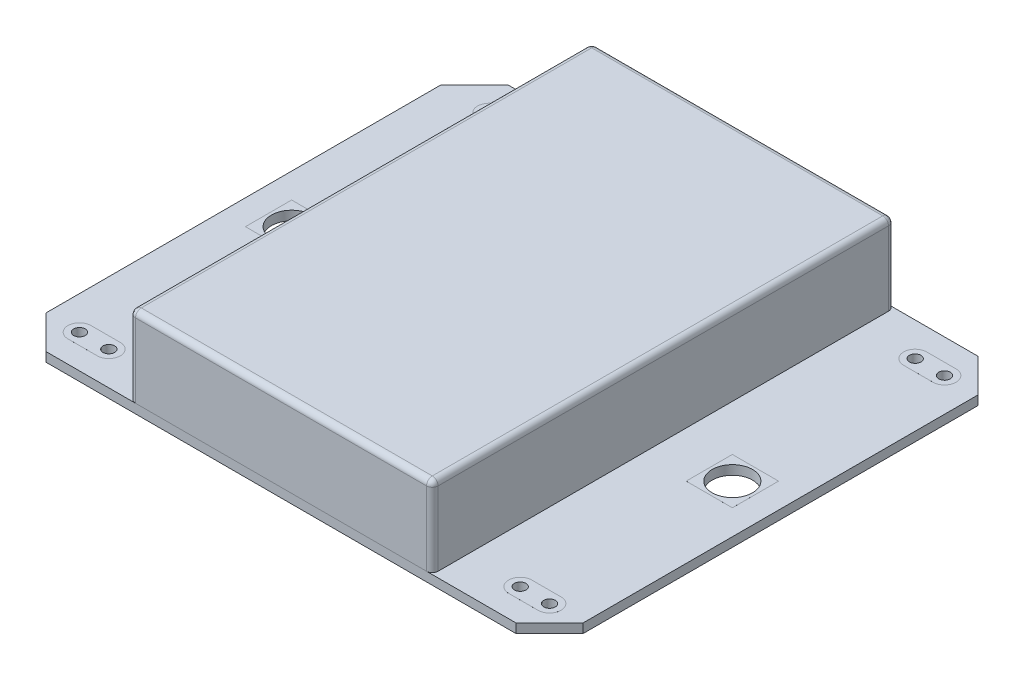
SolidWorks part; units mm, degrees
ref_plane "Front" through (0, 0, 0) normal (0, 0, 1) x (1, 0, 0)
ref_plane "Top" through (0, 0, 0) normal (0, 1, 0) x (1, 0, 0)
ref_plane "Right" through (0, 0, 0) normal (1, 0, 0) x (0, 0, -1)
sketch "Sketch1" plane through (0, 0, 0) normal (0, 1, 0) x (1, 0, 0)
  line L0 (-23.25, 17.1) -> (-20.35, 20)
  line L1 (-20.35, 20) -> (20.35, 20)
  line L2 (-23.25, 17.1) -> (-23.25, -17.1)
  line L3 (-20.35, -20) -> (20.35, -20)
  line L4 (23.25, 17.1) -> (23.25, -17.1)
  line L7 (20.35, 20) -> (23.25, 17.1)
  line L8 (20.35, -20) -> (23.25, -17.1)
  line L9 (-23.25, -17.1) -> (-20.35, -20)
  line L10 (0, 0) -> (0, -20) construction
  line L11 (-23.25, 0) -> (0, 0) construction
  line L12 (0, 0) -> (23.25, 0) construction
  line L13 (0, 20) -> (0, 0) construction
  point P0 (0, 0)
  dimension "D1" = 40.7
  dimension "D2" = 34.2
  dimension "D3" = 46.5
  dimension "D4" = 40
extrude "Boss-Extrude1" add sketch "Sketch1" along normal blind 0.8
sketch "Sketch2" plane through (0, 0.8, 0) normal (0, 1, 0) x (1, 0, 0)
  line L0 (20.35, 20) -> (-20.35, 20) construction
  line L1 (13.1, -20) -> (-13.1, -20)
  line L2 (13.1, -20) -> (13.1, 20)
  line L3 (13.1, 20) -> (-13.1, 20)
  line L4 (-13.1, -20) -> (-13.1, 20)
  line L5 (13.1, -20) -> (-13.1, 20) construction
  line L6 (13.1, 20) -> (-13.1, -20) construction
  point P0 (0, 0)
  dimension "D1" = 26.2
extrude "Boss-Extrude2" add sketch "Sketch2" along normal blind 6.9 separate body
fillet "Fillet1" radius 0.5 8 edges at (0, 7.7, -20) (13.1, 7.7, 0) (0, 7.7, 20) (-13.1, 7.7, 0) (13.1, 4.25, -20) (-13.1, 4.25, -20) (13.1, 4.25, 20) (-13.1, 4.25, 20)
sketch "Sketch3" plane through (0, 0.8, 0) normal (0, 1, 0) x (1, 0, 0)
  line L0 (17.81, 17.1) -> (20.35, 17.1) construction
  line L1 (17.81, 18.1) -> (20.35, 18.1)
  line L2 (17.81, 16.1) -> (20.35, 16.1)
  line L3 (17.81, -17.1) -> (20.35, -17.1) construction
  line L4 (17.81, -16.1) -> (20.35, -16.1)
  line L5 (17.81, -18.1) -> (20.35, -18.1)
  line L6 (-18.3274, 20) -> (-18.3274, 18.1) construction
  line L8 (20.35, 20) -> (-20.35, 20) construction
  line L10 (-19.08, 17.1) -> (-16.54, 17.1) construction
  line L11 (-19.08, 18.1) -> (-16.54, 18.1)
  line L12 (-19.08, 16.1) -> (-16.54, 16.1)
  line L13 (-20.35, -17.1) -> (-17.81, -17.1) construction
  line L14 (-20.35, -16.1) -> (-17.81, -16.1)
  line L15 (-20.35, -18.1) -> (-17.81, -18.1)
  line L16 (-19.08, 17.1) -> (-19.08, -17.1) construction
  line L17 (19.08, 17.1) -> (19.08, -17.1) construction
  line L20 (-23.25, 17.1) -> (-23.25, -17.1) construction
  line L22 (-18.3274, -18.1) -> (-18.3274, -20) construction
  line L23 (-20.35, -20) -> (20.35, -20) construction
  arc A0 (17.81, 18.1) -> (17.81, 16.1) centre (17.81, 17.1) ccw
  arc A1 (20.35, 16.1) -> (20.35, 18.1) centre (20.35, 17.1) ccw
  arc A2 (17.81, -16.1) -> (17.81, -18.1) centre (17.81, -17.1) ccw
  arc A3 (20.35, -18.1) -> (20.35, -16.1) centre (20.35, -17.1) ccw
  arc A4 (-19.08, 18.1) -> (-19.08, 16.1) centre (-19.08, 17.1) ccw
  arc A5 (-16.54, 16.1) -> (-16.54, 18.1) centre (-16.54, 17.1) ccw
  arc A6 (-20.35, -16.1) -> (-20.35, -18.1) centre (-20.35, -17.1) ccw
  arc A7 (-17.81, -18.1) -> (-17.81, -16.1) centre (-17.81, -17.1) ccw
  point P2 (19.08, 17.1)
  point P7 (19.08, -17.1)
  point P22 (-17.81, 17.1)
  point P29 (-19.08, -17.1)
  dimension "D6" = 1
  dimension "D7" = 1
  dimension "D8" = 1
  dimension "D9" = 1
  dimension "D1" = 34.2
  dimension "D2" = 35.62
  dimension "D3" = 40.7
  dimension "D4" = 5.44
  dimension "D5" = 2.54
  dimension "D10" = 2.54
extrude "Boss-Extrude3" add sketch "Sketch3" along normal blind 0.001
sketch "Sketch4" plane through (0, 0.801, 0) normal (0, 1, 0) x (1, 0, 0)
  circle A0 centre (-16.54, 17.1) radius 0.5
  circle A1 centre (-19.08, 17.1) radius 0.5
  circle A2 centre (20.35, 17.1) radius 0.5
  circle A3 centre (17.81, 17.1) radius 0.5
  circle A4 centre (20.35, -17.1) radius 0.5
  circle A5 centre (17.81, -17.1) radius 0.5
  circle A6 centre (-17.81, -17.1) radius 0.5
  circle A7 centre (-20.35, -17.1) radius 0.5
  dimension "D1" = 1
extrude "Cut-Extrude1" cut sketch "Sketch4" against normal blind 80.001
sketch "Sketch5" plane through (0, 0.8, 0) normal (0, 1, 0) x (1, 0, 0)
  line L0 (-19.08, 0) -> (19.08, 0) construction
  line L1 (-19.08, -16.1) -> (-19.08, 0) construction
  line L2 (-17.81, -16.1) -> (-20.35, -16.1) construction
  line L4 (-21.08, 2) -> (-17.08, 2)
  line L5 (-21.08, 2) -> (-21.08, -2)
  line L6 (-21.08, -2) -> (-17.08, -2)
  line L7 (-17.08, 2) -> (-17.08, -2)
  line L8 (-21.08, 2) -> (-17.08, -2) construction
  line L9 (-21.08, -2) -> (-17.08, 2) construction
  line L10 (17.08, 2) -> (21.08, 2)
  line L11 (17.08, 2) -> (17.08, -2)
  line L12 (17.08, -2) -> (21.08, -2)
  line L13 (21.08, 2) -> (21.08, -2)
  line L14 (17.08, 2) -> (21.08, -2) construction
  line L15 (17.08, -2) -> (21.08, 2) construction
  point P4 (0, 0)
  dimension "D1" = 4
extrude "Boss-Extrude4" add sketch "Sketch5" along normal blind 0.001
sketch "Sketch6" plane through (0, 0.801, 0) normal (0, 1, 0) x (1, 0, 0)
  line L0 (-19.08, 2) -> (-19.08, 0) construction
  line L1 (-17.08, 2) -> (-21.08, 2) construction
  line L2 (-19.08, 0) -> (-17.08, 0) construction
  line L3 (-17.08, -2) -> (-17.08, 2) construction
  line L4 (19.08, 2) -> (19.08, 0) construction
  line L5 (21.08, 2) -> (17.08, 2) construction
  line L6 (19.08, 0) -> (21.08, 0) construction
  line L7 (21.08, -2) -> (21.08, 2) construction
  circle A0 centre (-19.08, 0) radius 1.75
  circle A1 centre (19.08, 0) radius 1.75
  dimension "D1" = 3.5
extrude "Cut-Extrude2" cut sketch "Sketch6" against normal blind 70.001
